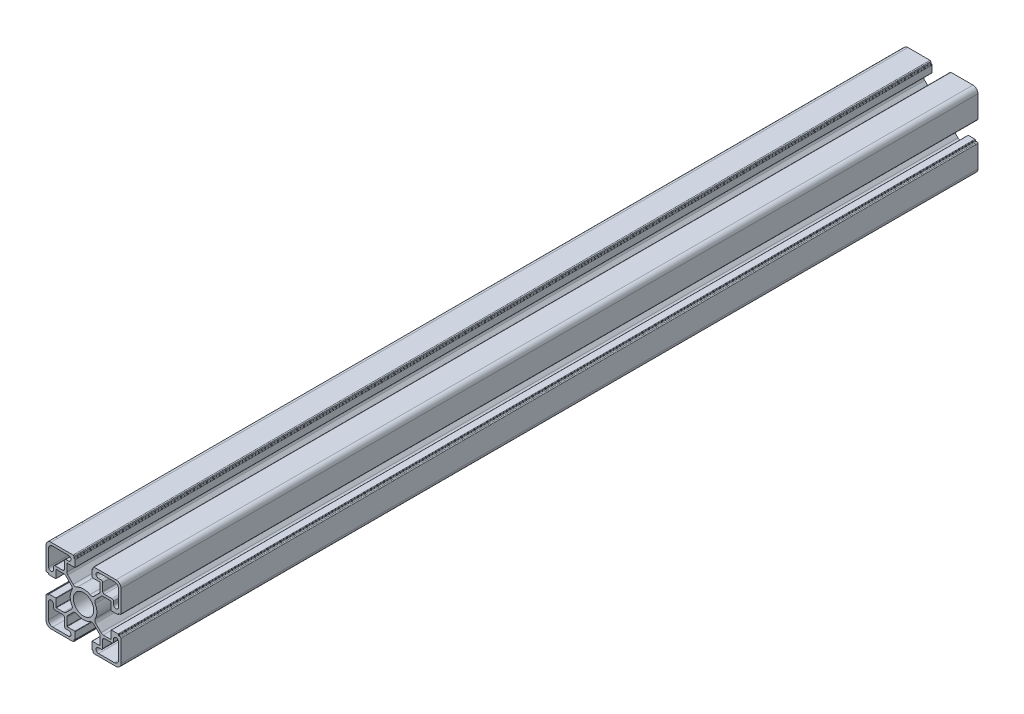
SolidWorks part; units mm, degrees
ref_plane "Front Plane" through (0, 0, 0) normal (0, 0, 1) x (1, 0, 0)
ref_plane "Top Plane" through (0, 0, 0) normal (0, 1, 0) x (1, 0, 0)
ref_plane "Right Plane" through (0, 0, 0) normal (1, 0, 0) x (0, 0, -1)
sketch "Sketch1" plane through (0, 0, 0) normal (0, 0, 1) x (1, 0, 0)
  line L3 (-22.5, 19.5) -> (-22.5, 6.3)
  line L4 (-20.7, 5) -> (-16.7, 5)
  line L5 (-16.5, 5.2) -> (-16.5, 9.8)
  line L6 (-16.3, 10) -> (-11.8642, 10)
  line L7 (-10.4924, 9.4318) -> (-7.2967, 6.236)
  line L8 (-21, 18.5) -> (-21, 9)
  line L9 (-16.5, 5) -> (-16.5, 10) construction
  line L10 (-18, 9) -> (-18, 10.5)
  line L11 (-17, 11.5) -> (-12.5, 11.5)
  line L12 (-22, 5.8) -> (-21.3, 5.8)
  line L13 (-21, 5.5) -> (-21, 5.3)
  line L14 (-21, 22.5) -> (-21, 6.5) construction
  line L15 (-18, 11.5) -> (-10.4393, 11.5) construction
  line L16 (-10.4393, 11.5) -> (-5.1016, 6.1623) construction
  line L17 (-18, 6.5) -> (-18, 11.5) construction
  line L18 (-22.5, 22.5) -> (-22.5, 5) construction
  line L19 (-22.5, 5) -> (-16.5, 5) construction
  line L20 (-21, 6.5) -> (-18, 6.5) construction
  line L21 (-16.5, 10) -> (-11.0607, 10) construction
  line L22 (-11.0607, 10) -> (-6.1623, 5.1016) construction
  line L23 (-5.5, 21) -> (-5.3, 21)
  line L24 (-5.8, 22) -> (-5.8, 21.3)
  line L25 (-11.5, 17) -> (-11.5, 12.5)
  line L26 (-9, 18) -> (-10.5, 18)
  line L27 (-18.5, 21) -> (-9, 21)
  line L28 (-9.4318, 10.4924) -> (-6.236, 7.2967)
  line L29 (-10, 16.3) -> (-10, 11.8642)
  line L30 (-5.2, 16.5) -> (-9.8, 16.5)
  line L31 (-5, 20.7) -> (-5, 16.7)
  line L32 (-19.5, 22.5) -> (-6.3, 22.5)
  line L33 (19.5, 22.5) -> (6.3, 22.5)
  line L34 (5, 20.7) -> (5, 16.7)
  line L35 (5.2, 16.5) -> (9.8, 16.5)
  line L36 (10, 16.3) -> (10, 11.8642)
  line L37 (9.4318, 10.4924) -> (6.236, 7.2967)
  line L38 (18.5, 21) -> (9, 21)
  line L39 (9, 18) -> (10.5, 18)
  line L40 (11.5, 17) -> (11.5, 12.5)
  line L41 (5.8, 22) -> (5.8, 21.3)
  line L42 (5.5, 21) -> (5.3, 21)
  line L43 (21, 5.5) -> (21, 5.3)
  line L44 (22, 5.8) -> (21.3, 5.8)
  line L45 (17, 11.5) -> (12.5, 11.5)
  line L46 (18, 9) -> (18, 10.5)
  line L47 (21, 18.5) -> (21, 9)
  line L48 (10.4924, 9.4318) -> (7.2967, 6.236)
  line L49 (16.3, 10) -> (11.8642, 10)
  line L50 (16.5, 5.2) -> (16.5, 9.8)
  line L51 (20.7, 5) -> (16.7, 5)
  line L52 (22.5, 19.5) -> (22.5, 6.3)
  line L53 (22.5, -19.5) -> (22.5, -6.3)
  line L54 (20.7, -5) -> (16.7, -5)
  line L55 (16.5, -5.2) -> (16.5, -9.8)
  line L56 (16.3, -10) -> (11.8642, -10)
  line L57 (10.4924, -9.4318) -> (7.2967, -6.236)
  line L58 (21, -18.5) -> (21, -9)
  line L59 (18, -9) -> (18, -10.5)
  line L60 (17, -11.5) -> (12.5, -11.5)
  line L61 (22, -5.8) -> (21.3, -5.8)
  line L62 (21, -5.5) -> (21, -5.3)
  line L63 (5.5, -21) -> (5.3, -21)
  line L64 (5.8, -22) -> (5.8, -21.3)
  line L65 (11.5, -17) -> (11.5, -12.5)
  line L66 (9, -18) -> (10.5, -18)
  line L67 (18.5, -21) -> (9, -21)
  line L68 (9.4318, -10.4924) -> (6.236, -7.2967)
  line L69 (10, -16.3) -> (10, -11.8642)
  line L70 (5.2, -16.5) -> (9.8, -16.5)
  line L71 (5, -20.7) -> (5, -16.7)
  line L72 (19.5, -22.5) -> (6.3, -22.5)
  line L73 (-19.5, -22.5) -> (-6.3, -22.5)
  line L74 (-5, -20.7) -> (-5, -16.7)
  line L75 (-5.2, -16.5) -> (-9.8, -16.5)
  line L76 (-10, -16.3) -> (-10, -11.8642)
  line L77 (-9.4318, -10.4924) -> (-6.236, -7.2967)
  line L78 (-18.5, -21) -> (-9, -21)
  line L79 (-9, -18) -> (-10.5, -18)
  line L80 (-11.5, -17) -> (-11.5, -12.5)
  line L81 (-5.8, -22) -> (-5.8, -21.3)
  line L82 (-5.5, -21) -> (-5.3, -21)
  line L83 (-21, -5.5) -> (-21, -5.3)
  line L84 (-22, -5.8) -> (-21.3, -5.8)
  line L85 (-17, -11.5) -> (-12.5, -11.5)
  line L86 (-18, -9) -> (-18, -10.5)
  line L87 (-21, -18.5) -> (-21, -9)
  line L88 (-10.4924, -9.4318) -> (-7.2967, -6.236)
  line L89 (-16.3, -10) -> (-11.8642, -10)
  line L90 (-16.5, -5.2) -> (-16.5, -9.8)
  line L91 (-20.7, -5) -> (-16.7, -5)
  line L92 (-22.5, -19.5) -> (-22.5, -6.3)
  arc A0 (0, 6.1) -> (-6.1, 0) centre (0, 0) ccw
  arc A1 (-6.9766, 3.9149) -> (-8, 0) centre (0, 0) ccw
  arc A2 (-21, 9) -> (-18, 9) centre (-19.5, 9) ccw
  arc A3 (-22, 5.8) -> (-22.5, 6.3) centre (-22, 6.3) cw
  arc A4 (-21, 5.3) -> (-20.7, 5) centre (-20.7, 5.3) ccw
  arc A5 (-21.3, 5.8) -> (-21, 5.5) centre (-21.3, 5.5) cw
  arc A6 (-16.7, 5) -> (-16.5, 5.2) centre (-16.7, 5.2) ccw
  arc A7 (-16.5, 9.8) -> (-16.3, 10) centre (-16.3, 9.8) cw
  arc A8 (-7.2967, 6.236) -> (-6.9766, 3.9149) centre (-8.6685, 4.8643) cw
  arc A9 (-11.8642, 10) -> (-10.4924, 9.4318) centre (-11.8642, 8.06) cw
  arc A10 (-18, 10.5) -> (-17, 11.5) centre (-17, 10.5) cw
  arc A11 (-10.5, 18) -> (-11.5, 17) centre (-10.5, 17) ccw
  arc A12 (-10, 11.8642) -> (-9.4318, 10.4924) centre (-8.06, 11.8642) ccw
  arc A13 (-6.236, 7.2967) -> (-3.9149, 6.9766) centre (-4.8643, 8.6685) ccw
  arc A14 (-9.8, 16.5) -> (-10, 16.3) centre (-9.8, 16.3) ccw
  arc A15 (-5, 16.7) -> (-5.2, 16.5) centre (-5.2, 16.7) cw
  arc A16 (-5.8, 21.3) -> (-5.5, 21) centre (-5.5, 21.3) ccw
  arc A17 (-5.3, 21) -> (-5, 20.7) centre (-5.3, 20.7) cw
  arc A18 (-5.8, 22) -> (-6.3, 22.5) centre (-6.3, 22) ccw
  arc A19 (-9, 21) -> (-9, 18) centre (-9, 19.5) cw
  arc A20 (-3.9149, 6.9766) -> (0, 8) centre (0, 0) cw
  arc A21 (-21, 18.5) -> (-18.5, 21) centre (-18.5, 18.5) cw
  arc A22 (-22.5, 19.5) -> (-19.5, 22.5) centre (-19.5, 19.5) cw
  arc A23 (-12.5, 11.5) -> (-11.5, 12.5) centre (-12.5, 12.5) ccw
  arc A24 (6.1, 0) -> (0, 6.1) centre (0, 0) ccw
  arc A25 (3.9149, 6.9766) -> (0, 8) centre (0, 0) ccw
  arc A26 (9, 21) -> (9, 18) centre (9, 19.5) ccw
  arc A27 (5.8, 22) -> (6.3, 22.5) centre (6.3, 22) cw
  arc A28 (5.3, 21) -> (5, 20.7) centre (5.3, 20.7) ccw
  arc A29 (5.8, 21.3) -> (5.5, 21) centre (5.5, 21.3) cw
  arc A30 (5, 16.7) -> (5.2, 16.5) centre (5.2, 16.7) ccw
  arc A31 (9.8, 16.5) -> (10, 16.3) centre (9.8, 16.3) cw
  arc A32 (6.236, 7.2967) -> (3.9149, 6.9766) centre (4.8643, 8.6685) cw
  arc A33 (10, 11.8642) -> (9.4318, 10.4924) centre (8.06, 11.8642) cw
  arc A34 (10.5, 18) -> (11.5, 17) centre (10.5, 17) cw
  arc A35 (18, 10.5) -> (17, 11.5) centre (17, 10.5) ccw
  arc A36 (11.8642, 10) -> (10.4924, 9.4318) centre (11.8642, 8.06) ccw
  arc A37 (7.2967, 6.236) -> (6.9766, 3.9149) centre (8.6685, 4.8643) ccw
  arc A38 (16.5, 9.8) -> (16.3, 10) centre (16.3, 9.8) ccw
  arc A39 (16.7, 5) -> (16.5, 5.2) centre (16.7, 5.2) cw
  arc A40 (21.3, 5.8) -> (21, 5.5) centre (21.3, 5.5) ccw
  arc A41 (21, 5.3) -> (20.7, 5) centre (20.7, 5.3) cw
  arc A42 (22, 5.8) -> (22.5, 6.3) centre (22, 6.3) ccw
  arc A43 (21, 9) -> (18, 9) centre (19.5, 9) cw
  arc A44 (6.9766, 3.9149) -> (8, 0) centre (0, 0) cw
  arc A45 (18.5, 21) -> (21, 18.5) centre (18.5, 18.5) cw
  arc A46 (19.5, 22.5) -> (22.5, 19.5) centre (19.5, 19.5) cw
  arc A47 (11.5, 12.5) -> (12.5, 11.5) centre (12.5, 12.5) ccw
  arc A48 (0, -6.1) -> (6.1, 0) centre (0, 0) ccw
  arc A49 (6.9766, -3.9149) -> (8, 0) centre (0, 0) ccw
  arc A50 (21, -9) -> (18, -9) centre (19.5, -9) ccw
  arc A51 (22, -5.8) -> (22.5, -6.3) centre (22, -6.3) cw
  arc A52 (21, -5.3) -> (20.7, -5) centre (20.7, -5.3) ccw
  arc A53 (21.3, -5.8) -> (21, -5.5) centre (21.3, -5.5) cw
  arc A54 (16.7, -5) -> (16.5, -5.2) centre (16.7, -5.2) ccw
  arc A55 (16.5, -9.8) -> (16.3, -10) centre (16.3, -9.8) cw
  arc A56 (7.2967, -6.236) -> (6.9766, -3.9149) centre (8.6685, -4.8643) cw
  arc A57 (11.8642, -10) -> (10.4924, -9.4318) centre (11.8642, -8.06) cw
  arc A58 (18, -10.5) -> (17, -11.5) centre (17, -10.5) cw
  arc A59 (10.5, -18) -> (11.5, -17) centre (10.5, -17) ccw
  arc A60 (10, -11.8642) -> (9.4318, -10.4924) centre (8.06, -11.8642) ccw
  arc A61 (6.236, -7.2967) -> (3.9149, -6.9766) centre (4.8643, -8.6685) ccw
  arc A62 (9.8, -16.5) -> (10, -16.3) centre (9.8, -16.3) ccw
  arc A63 (5, -16.7) -> (5.2, -16.5) centre (5.2, -16.7) cw
  arc A64 (5.8, -21.3) -> (5.5, -21) centre (5.5, -21.3) ccw
  arc A65 (5.3, -21) -> (5, -20.7) centre (5.3, -20.7) cw
  arc A66 (5.8, -22) -> (6.3, -22.5) centre (6.3, -22) ccw
  arc A67 (9, -21) -> (9, -18) centre (9, -19.5) cw
  arc A68 (3.9149, -6.9766) -> (0, -8) centre (0, 0) cw
  arc A69 (21, -18.5) -> (18.5, -21) centre (18.5, -18.5) cw
  arc A70 (22.5, -19.5) -> (19.5, -22.5) centre (19.5, -19.5) cw
  arc A71 (12.5, -11.5) -> (11.5, -12.5) centre (12.5, -12.5) ccw
  arc A72 (-6.1, 0) -> (0, -6.1) centre (0, 0) ccw
  arc A73 (-3.9149, -6.9766) -> (0, -8) centre (0, 0) ccw
  arc A74 (-9, -21) -> (-9, -18) centre (-9, -19.5) ccw
  arc A75 (-5.8, -22) -> (-6.3, -22.5) centre (-6.3, -22) cw
  arc A76 (-5.3, -21) -> (-5, -20.7) centre (-5.3, -20.7) ccw
  arc A77 (-5.8, -21.3) -> (-5.5, -21) centre (-5.5, -21.3) cw
  arc A78 (-5, -16.7) -> (-5.2, -16.5) centre (-5.2, -16.7) ccw
  arc A79 (-9.8, -16.5) -> (-10, -16.3) centre (-9.8, -16.3) cw
  arc A80 (-6.236, -7.2967) -> (-3.9149, -6.9766) centre (-4.8643, -8.6685) cw
  arc A81 (-10, -11.8642) -> (-9.4318, -10.4924) centre (-8.06, -11.8642) cw
  arc A82 (-10.5, -18) -> (-11.5, -17) centre (-10.5, -17) cw
  arc A83 (-18, -10.5) -> (-17, -11.5) centre (-17, -10.5) ccw
  arc A84 (-11.8642, -10) -> (-10.4924, -9.4318) centre (-11.8642, -8.06) ccw
  arc A85 (-7.2967, -6.236) -> (-6.9766, -3.9149) centre (-8.6685, -4.8643) ccw
  arc A86 (-16.5, -9.8) -> (-16.3, -10) centre (-16.3, -9.8) ccw
  arc A87 (-16.7, -5) -> (-16.5, -5.2) centre (-16.7, -5.2) cw
  arc A88 (-21.3, -5.8) -> (-21, -5.5) centre (-21.3, -5.5) ccw
  arc A89 (-21, -5.3) -> (-20.7, -5) centre (-20.7, -5.3) cw
  arc A90 (-22, -5.8) -> (-22.5, -6.3) centre (-22, -6.3) ccw
  arc A91 (-21, -9) -> (-18, -9) centre (-19.5, -9) cw
  arc A92 (-6.9766, -3.9149) -> (-8, 0) centre (0, 0) cw
  arc A93 (-18.5, -21) -> (-21, -18.5) centre (-18.5, -18.5) cw
  arc A94 (-19.5, -22.5) -> (-22.5, -19.5) centre (-19.5, -19.5) cw
  arc A95 (-11.5, -12.5) -> (-12.5, -11.5) centre (-12.5, -12.5) ccw
  point P24 (-5.8, 21)
  point P32 (-22.5, 5.8)
  point P35 (-21, 5)
  point P38 (-21, 5.8)
  point P83 (-5, 21)
  point P84 (-5.8, 22.5)
  point P87 (-21, 21)
  point P93 (-11.5, 11.5)
  point P102 (21, 5.8)
  point P158 (21, 5)
  point P159 (22.5, 5.8)
  point P172 (5.8, -21)
  point P228 (5, -21)
  point P229 (5.8, -22.5)
  point P242 (-21, -5.8)
  point P298 (-21, -5)
  point P299 (-22.5, -5.8)
  dimension "D11" = 0.5
  dimension "D12" = 0.3
  dimension "D13" = 0.2
  dimension "D14" = 0.2
  dimension "D6" = 1.94
  dimension "D15" = 1
  dimension "D16" = 2.5
  dimension "D4" = 3
  dimension "D17" = 1
  dimension "D5" = 0.8
  dimension "D7" = 1.5
  dimension "D9" = 1.5
  dimension "D10" = 4
  dimension "D18" = 4
extrude "Boss-Extrude1" add sketch "Sketch1" along normal blind 513.778
scale "Scale1" scale about centroid uniform scaling yes scale factor 0.564444
